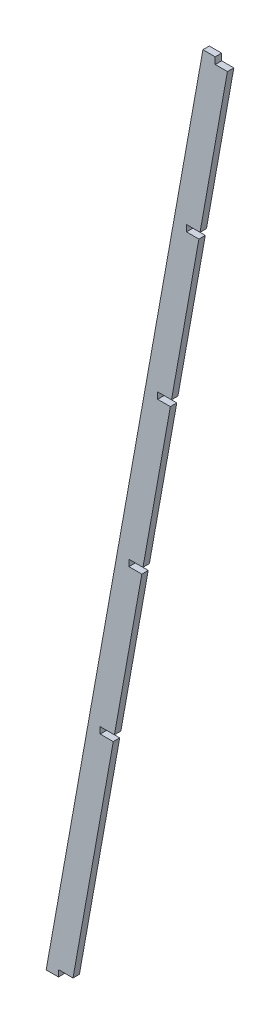
SolidWorks part; units mm, degrees
ref_plane "Front Plane" through (0, 0, 0) normal (0, 0, 1) x (1, 0, 0)
ref_plane "Top Plane" through (0, 0, 0) normal (0, 1, 0) x (1, 0, 0)
ref_plane "Right Plane" through (0, 0, 0) normal (1, 0, 0) x (0, 0, -1)
sketch "Sketch1" plane through (0, 0, 0) normal (0, 1, 0) x (1, 0, 0)
  line L1 (0, 0) -> (12.7, 0)
  line L2 (0, 0) -> (0, 3.175)
  line L3 (0, 3.175) -> (12.7, 3.175)
  line L4 (12.7, 0) -> (12.7, 3.175)
  point P7 (0, 4.1109)
  dimension "D1" = 12.7
  dimension "D2" = 3.175
ref_plane "Plane1" through (0, 432.562, 0) normal (0, 1, 0) x (1, 0, 0)
sketch "Sketch2" plane through (0, 432.562, 0) normal (0, 1, 0) x (1, 0, 0)
  line L1 (77.47, 0) -> (90.17, 0)
  line L2 (77.47, 0) -> (77.47, 3.175)
  line L3 (77.47, 3.175) -> (90.17, 3.175)
  line L4 (90.17, 0) -> (90.17, 3.175)
  point P4 (20.6473, -2.4093)
  point P5 (16.8467, 2.444)
  dimension "D1" = 12.7
  dimension "D2" = 3.175
  dimension "D3" = 0
  dimension "D4" = 77.47
loft "Loft1" add profiles "Sketch1", "Sketch2"
sketch "Sketch3" plane through (0, 0, 0) normal (0, 0, 1) x (1, 0, 0)
  line L0 (83.5418, 432.562) -> (83.5418, 429.26)
  line L9 (6.0718, 3.175) -> (6.0718, 0)
  line L10 (77.47, 432.562) -> (90.17, 432.562) construction
  line L11 (89.5786, 429.26) -> (83.5418, 429.26)
  line L12 (12.7, 0) -> (90.17, 432.562) construction
  line L13 (83.5418, 432.562) -> (90.17, 432.562)
  line L14 (90.17, 432.562) -> (89.5786, 429.26)
  line L15 (26.6999, 117.475) -> (26.6999, 114.3)
  line L16 (69.3313, 353.695) -> (69.3313, 350.52)
  line L17 (69.3313, 353.695) -> (76.0453, 353.695)
  line L18 (69.3313, 350.52) -> (75.4766, 350.52)
  line L19 (75.4766, 350.52) -> (76.0453, 353.695)
  line L20 (55.1209, 274.955) -> (55.1209, 271.78)
  line L21 (40.9104, 193.04) -> (40.9104, 196.215)
  line L22 (55.1209, 271.78) -> (61.3746, 271.78)
  line L23 (61.3746, 271.78) -> (61.9433, 274.955)
  line L24 (61.9433, 274.955) -> (55.1209, 274.955)
  line L25 (47.8413, 196.215) -> (47.2726, 193.04)
  line L26 (47.2726, 193.04) -> (40.9104, 193.04)
  line L27 (40.9104, 196.215) -> (47.8413, 196.215)
  line L28 (33.1706, 114.3) -> (33.7393, 117.475)
  line L29 (33.7393, 117.475) -> (26.6999, 117.475)
  line L30 (26.6999, 114.3) -> (33.1706, 114.3)
  line L31 (6.0718, 0) -> (12.7, 0)
  line L32 (12.7, 0) -> (13.2686, 3.175)
  line L33 (13.2686, 3.175) -> (6.0718, 3.175)
extrude "Cut-Extrude1" cut sketch "Sketch3" against normal blind 5.08
